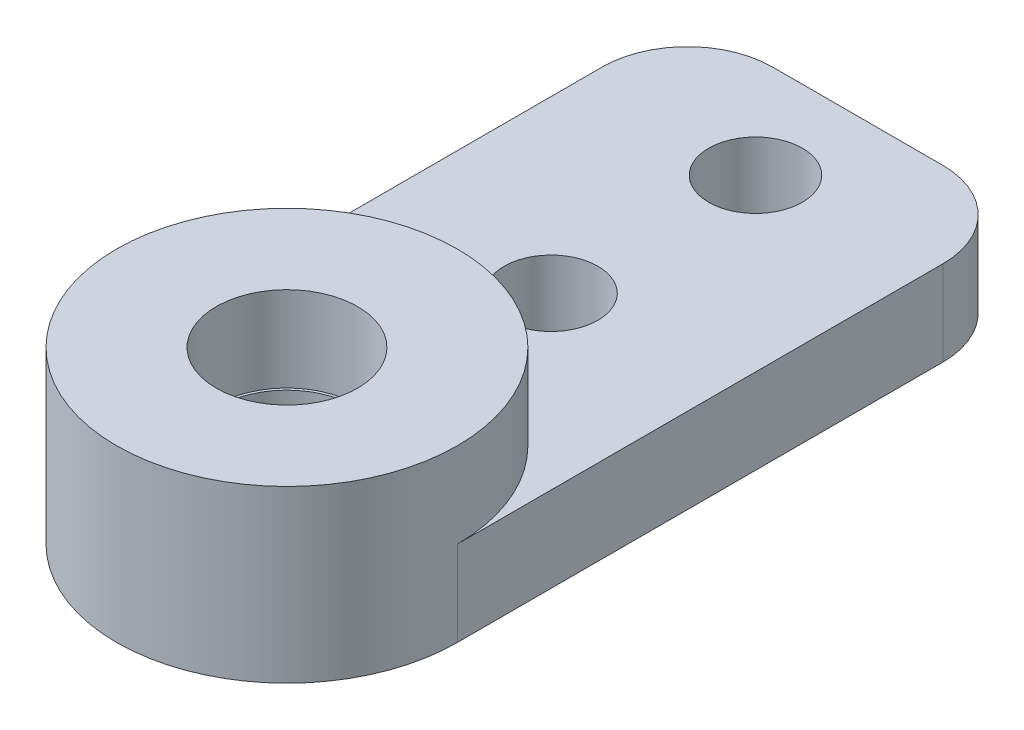
SolidWorks part; units mm, degrees
ref_plane "前视基准面" through (0, 0, 0) normal (0, 0, 1) x (1, 0, 0)
ref_plane "上视基准面" through (0, 0, 0) normal (0, 1, 0) x (1, 0, 0)
ref_plane "右视基准面" through (0, 0, 0) normal (1, 0, 0) x (0, 0, -1)
sketch "草图1" plane through (0, 0, 0) normal (0, 1, 0) x (1, 0, 0)
  line L0 (10, 0) -> (10, 33.5)
  line L1 (-10, 0) -> (-10, 33.5)
  line L2 (-10, 33.5) -> (10, 33.5)
  arc A0 (-10, 0) -> (10, 0) centre (0, 0) ccw
  circle A1 centre (0, 27.5) radius 2.75
  circle A2 centre (0, 15.5) radius 2.75
  circle A3 centre (0, 0) radius 4
  point P12 (-1.6546, 15.5)
  point P13 (0, 0)
  dimension "D1" = 20
  dimension "D3" = 5.5
  dimension "D5" = 5.5
  dimension "D7" = 8
  dimension "D2" = 33.5
  dimension "D4" = 6
  dimension "D6" = 12
  dimension "D8" = 0
  dimension "D9" = 0
extrude "凸台-拉伸1" add sketch "草图1" along normal blind 5
sketch "草图2" plane through (0, 5, 0) normal (0, 1, 0) x (1, 0, 0)
  circle A0 centre (0, 0) radius 10
  arc A1 (-10, 0) -> (10, 0) centre (0, 0) ccw construction
  circle A2 centre (0, 0) radius 4.15
  dimension "D1" = 20
  dimension "D2" = 8.3
extrude "凸台-拉伸2" add sketch "草图2" along normal blind 5
fillet "圆角1" radius 5 2 edges at (10, 2.5, -33.5) (-10, 2.5, -33.5)
